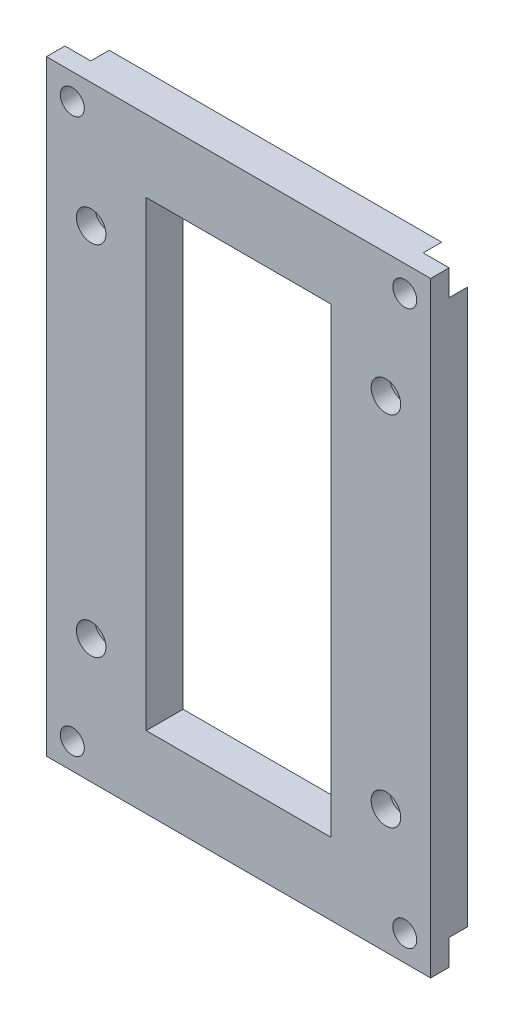
SolidWorks part; units mm, degrees
ref_plane "Front Plane" through (0, 0, 0) normal (0, 0, 1) x (1, 0, 0)
ref_plane "Top Plane" through (0, 0, 0) normal (0, 1, 0) x (1, 0, 0)
ref_plane "Right Plane" through (0, 0, 0) normal (1, 0, 0) x (0, 0, -1)
sketch "Sketch1" plane through (0, 0, 0) normal (0, 0, 1) x (1, 0, 0)
  line L1 (45, -75) -> (-45, -75)
  line L2 (45, -75) -> (45, 75)
  line L3 (45, 75) -> (-45, 75)
  line L4 (-45, -75) -> (-45, 75)
  line L5 (45, -75) -> (-45, 75) construction
  line L6 (45, 75) -> (-45, -75) construction
  line L7 (52, -82) -> (-52, -82)
  line L8 (52, -82) -> (52, 82)
  line L9 (52, 82) -> (-52, 82)
  line L10 (-52, -82) -> (-52, 82)
  line L11 (52, -82) -> (-52, 82) construction
  line L12 (52, 82) -> (-52, -82) construction
  circle A0 centre (-45, 75) radius 3.25
  circle A1 centre (45, 75) radius 3.25
  circle A2 centre (-45, -75) radius 3.25
  circle A3 centre (45, -75) radius 3.25
  point P0 (0, 0)
  point P6 (0, 0)
  dimension "D5" = 6.5
  dimension "D6" = 6.5
  dimension "D7" = 6.5
  dimension "D8" = 6.5
  dimension "D1" = 90
  dimension "D2" = 150
  dimension "D3" = 7
  dimension "D4" = 7
extrude "Boss-Extrude1" add sketch "Sketch1" along normal blind 10 contours L10 L7 L8 L9 A3 L1 A2 L4 A0 L3 A1 L2 | A3 L2 A1 L3 A0 L4 A2 L1
sketch "Sketch2" plane through (0, 0, 0) normal (0, 0, -1) x (-1, 0, 0)
  line L1 (39.9, -48.4) -> (-39.9, -48.4)
  line L2 (39.9, -48.4) -> (39.9, 48.4)
  line L3 (39.9, 48.4) -> (-39.9, 48.4)
  line L4 (-39.9, -48.4) -> (-39.9, 48.4)
  line L5 (39.9, -48.4) -> (-39.9, 48.4) construction
  line L6 (39.9, 48.4) -> (-39.9, -48.4) construction
  circle A0 centre (-39.9, 48.4) radius 1.625
  circle A1 centre (39.9, 48.4) radius 1.625
  circle A2 centre (-39.9, -48.4) radius 1.625
  circle A3 centre (39.9, -48.4) radius 1.625
  point P0 (0, 0)
  dimension "D3" = 3.25
  dimension "D4" = 3.25
  dimension "D5" = 3.25
  dimension "D6" = 3.25
  dimension "D1" = 79.8
  dimension "D2" = 96.8
extrude "Cut-Extrude1" cut sketch "Sketch2" against normal blind 10 contours A0 | A1 | A2 | A3
sketch "Sketch3" plane through (0, 0, 10) normal (0, 0, 1) x (1, 0, 0)
  circle A0 centre (-39.9, 48.4) radius 4
  circle A1 centre (39.9, 48.4) radius 4
  circle A2 centre (-39.9, -48.4) radius 4
  circle A3 centre (39.9, -48.4) radius 4
  dimension "D1" = 8
  dimension "D2" = 8
  dimension "D3" = 8
  dimension "D4" = 8
extrude "Cut-Extrude2" cut sketch "Sketch3" against normal blind 5
sketch "Sketch5" plane through (0, 0, 0) normal (0, 0, -1) x (-1, 0, 0)
  line L1 (-52, 82) -> (52, 82)
  line L2 (-52, 82) -> (-52, -82)
  line L3 (-52, -82) -> (52, -82)
  line L4 (52, 82) -> (52, -82)
  circle A0 centre (-45, 75) radius 7
  circle A1 centre (45, 75) radius 7
  circle A2 centre (45, -75) radius 7
  circle A3 centre (-45, -75) radius 7
  circle M5 centre (45, -75) radius 3.25
  circle M6 centre (45, 75) radius 3.25
  circle M7 centre (-45, -75) radius 3.25
  circle M8 centre (-45, 75) radius 3.25
  line M9 (52, -82) -> (52, 82)
  line M10 (52, 82) -> (-52, 82)
  line M11 (-52, 82) -> (-52, -82)
  line M12 (-52, -82) -> (52, -82)
extrude "Cut-Extrude3" cut sketch "Sketch5" against normal blind 5 contours A0 M8 | A0 L1 M11 | A1 M6 | A1 L4 M10 | A3 M7 | A2 M5 | A2 L3 M9 | A3 M11 M12
sketch "Sketch6" plane through (0, 0, 0) normal (0, 0, -1) x (-1, 0, 0)
  line L1 (25, -62.5) -> (-25, -62.5)
  line L2 (25, -62.5) -> (25, 62.5)
  line L3 (25, 62.5) -> (-25, 62.5)
  line L4 (-25, -62.5) -> (-25, 62.5)
  line L5 (25, -62.5) -> (-25, 62.5) construction
  line L6 (25, 62.5) -> (-25, -62.5) construction
  point P0 (0, 0)
  dimension "D1" = 50
  dimension "D2" = 125
extrude "Cut-Extrude4" cut sketch "Sketch6" against normal blind 52
